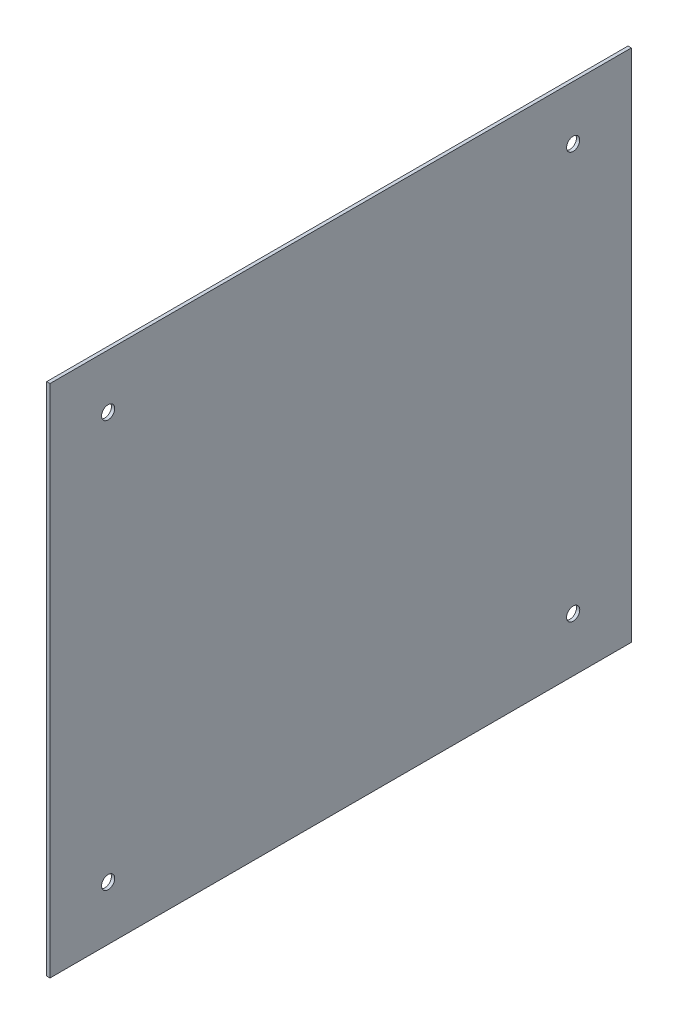
SolidWorks part; units mm, degrees
material "3003 Alloy"
ref_plane "Front Plane" through (0, 0, 0) normal (0, 0, 1) x (1, 0, 0)
ref_plane "Top Plane" through (0, 0, 0) normal (0, 1, 0) x (1, 0, 0)
ref_plane "Right Plane" through (0, 0, 0) normal (1, 0, 0) x (0, 0, -1)
sketch "Sketch1" plane through (0, 0, 0) normal (1, 0, 0) x (0, 0, -1)
  line L1 (175, -155) -> (-175, -155)
  line L2 (175, -155) -> (175, 155)
  line L3 (175, 155) -> (-175, 155)
  line L4 (-175, -155) -> (-175, 155)
  line L5 (175, -155) -> (-175, 155) construction
  line L6 (175, 155) -> (-175, -155) construction
  point P0 (0, 0)
  dimension "D1" = 350
  dimension "D2" = 310
extrude "Boss-Extrude1" add sketch "Sketch1" along normal blind 2
sketch "Sketch2" plane through (2, 0, 0) normal (1, 0, 0) x (0, 0, -1)
  line L0 (175, 155) -> (-175, 155) construction
  line L1 (-175, 155) -> (-175, -155) construction
  line L2 (0, 155) -> (0, -155) construction
  line L3 (-175, -155) -> (175, -155) construction
  line L4 (-175, 0) -> (175, 0) construction
  line L5 (175, -155) -> (175, 155) construction
  circle A0 centre (-140, 122.5) radius 3.97
  circle A1 centre (-140, -122.5) radius 3.97
  circle A2 centre (140, -122.5) radius 3.97
  circle A3 centre (140, 122.5) radius 3.97
  dimension "D1" = 7.94
  dimension "D2" = 32.5
  dimension "D3" = 35
extrude "Cut-Extrude1" cut sketch "Sketch2" against normal through all
